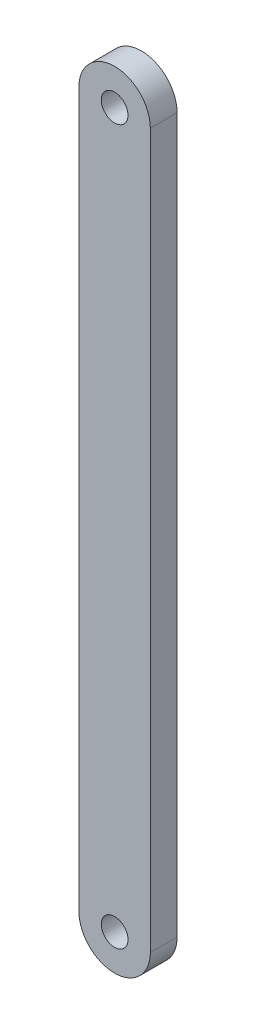
SolidWorks part; units mm, degrees
ref_plane "前基準面" through (0, 0, 0) normal (0, 0, 1) x (1, 0, 0)
ref_plane "上基準面" through (0, 0, 0) normal (0, 1, 0) x (1, 0, 0)
ref_plane "右基準面" through (0, 0, 0) normal (1, 0, 0) x (0, 0, -1)
sketch "草圖1" plane through (0, 0, 0) normal (0, 0, 1) x (1, 0, 0)
  line L0 (40.3001, 5) -> (40.3001, 85.0001)
  line L1 (48.3001, 85) -> (48.3001, 5)
  circle A0 centre (44.3001, 5) radius 1.5 construction
  arc A1 (48.3001, 85) -> (40.3001, 85.0001) centre (44.3001, 85) ccw construction
  circle A2 centre (44.3001, 85) radius 1.5 construction
  circle A3 centre (44.3001, 5) radius 1.5
  arc A4 (48.3001, 85) -> (40.3001, 85.0001) centre (44.3001, 85) ccw
  circle A5 centre (44.3001, 85) radius 1.5
  spline S0 degree 3 poles (40.3001, 5) (40.3001, 2.6569) (41.957, 1) (44.3001, 1) (46.6432, 1) (48.3001, 2.6569) (48.3001, 5) knots 0 0 0 0 0.5 0.5 0.5 1 1 1 1 weights 1 0.804738 0.804738 1 0.804738 0.804738 1 construction
  spline S1 degree 3 poles (40.3001, 5) (40.3001, 2.6569) (41.957, 1) (44.3001, 1) (46.6432, 1) (48.3001, 2.6569) (48.3001, 5) knots 0 0 0 0 0.5 0.5 0.5 1 1 1 1 weights 1 0.804738 0.804738 1 0.804738 0.804738 1
extrude "填料-伸長1" add sketch "草圖1" along normal blind 3
